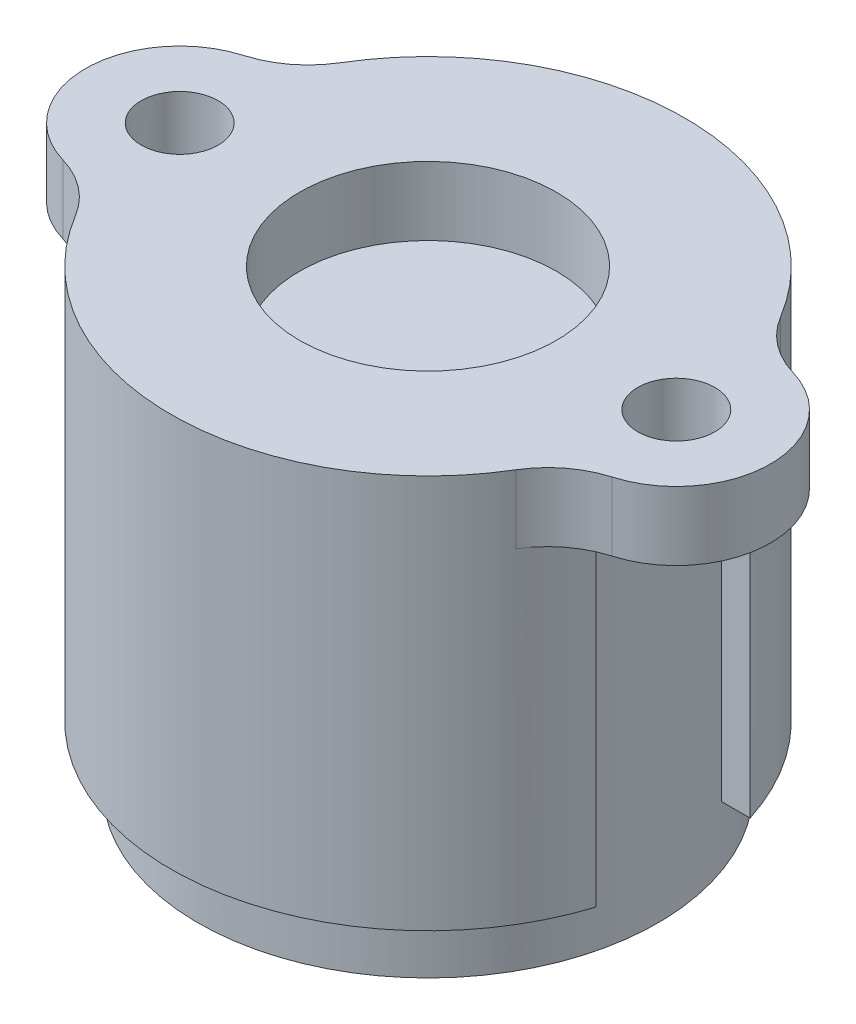
SolidWorks part; units mm, degrees
material "Polyethylene Cross-Linked"
ref_plane "Front Plane" through (0, 0, 0) normal (0, 0, 1) x (1, 0, 0)
ref_plane "Top Plane" through (0, 0, 0) normal (0, 1, 0) x (1, 0, 0)
ref_plane "Right Plane" through (0, 0, 0) normal (1, 0, 0) x (0, 0, -1)
sketch "Sketch1" plane through (0, 0, 0) normal (0, 1, 0) x (1, 0, 0)
  line L0 (7.366, 0) -> (-7.366, 0) construction
  arc A0 (-6.5305, -3.9264) -> (6.5305, -3.9264) centre (0, 0) ccw
  arc A1 (-8.1455, 2.6831) -> (-8.1455, -2.6831) centre (-7.366, 0) ccw
  arc A2 (8.1455, -2.6831) -> (8.1455, 2.6831) centre (7.366, 0) ccw
  arc A3 (6.5305, 3.9264) -> (-6.5305, 3.9264) centre (0, 0) ccw
  arc A4 (6.5305, 3.9264) -> (8.1455, 2.6831) centre (8.925, 5.3661) ccw
  arc A5 (6.5305, -3.9264) -> (8.1455, -2.6831) centre (8.925, -5.3661) cw
  arc A6 (-6.5305, -3.9264) -> (-8.1455, -2.6831) centre (-8.925, -5.3661) ccw
  arc A7 (-8.1455, 2.6831) -> (-6.5305, 3.9264) centre (-8.925, 5.3661) ccw
  point P6 (0, 0)
  point P11 (7.0945, 2.7808)
  dimension "D1" = 15.24
  dimension "D3" = 5.588
  dimension "D4" = 5.588
  dimension "D5" = 2.794
  dimension "D2" = 14.732
extrude "Boss-Extrude1" add sketch "Sketch1" along normal blind 2.032
sketch "Sketch2" plane through (0, 2.032, 0) normal (0, 1, 0) x (1, 0, 0)
  line L0 (7.366, 0) -> (-7.366, 0) construction
  circle A0 centre (0, 0) radius 3.81
  circle A1 centre (-7.366, 0) radius 1.143
  circle A2 centre (7.366, 0) radius 1.143
  point P6 (0, 0)
  dimension "D2" = 2.286
  dimension "D3" = 7.62
  dimension "D1" = 14.732
extrude "Cut-Extrude1" cut sketch "Sketch2" against normal through all
sketch "Sketch3" plane through (0, 0, 0) normal (0, -1, 0) x (1, 0, 0)
  circle A0 centre (0, 0) radius 7.62
  circle A1 centre (0, 0) radius 6.82
  dimension "D1" = 15.24
  dimension "D2" = 0.8
extrude "Boss-Extrude2" add sketch "Sketch3" along normal blind 9.652
sketch "Sketch4" plane through (0, 0, 0) normal (0, -1, 0) x (1, 0, 0)
  line L1 (-12.9144, -2.286) -> (12.9144, -2.286)
  line L2 (-12.9144, -2.286) -> (-12.9144, 2.286)
  line L3 (-12.9144, 2.286) -> (12.9144, 2.286)
  line L4 (12.9144, -2.286) -> (12.9144, 2.286)
  line L5 (-12.9144, -2.286) -> (12.9144, 2.286) construction
  line L6 (-12.9144, 2.286) -> (12.9144, -2.286) construction
  point P0 (0, 0)
  dimension "D1" = 4.572
extrude "Cut-Extrude2" cut sketch "Sketch4" along normal through all
sketch "Sketch5" plane through (0, 0, 0) normal (0, -1, 0) x (1, 0, 0)
  circle A0 centre (0, 0) radius 6.82
extrude "Boss-Extrude3" add sketch "Sketch5" along normal blind 11.43
